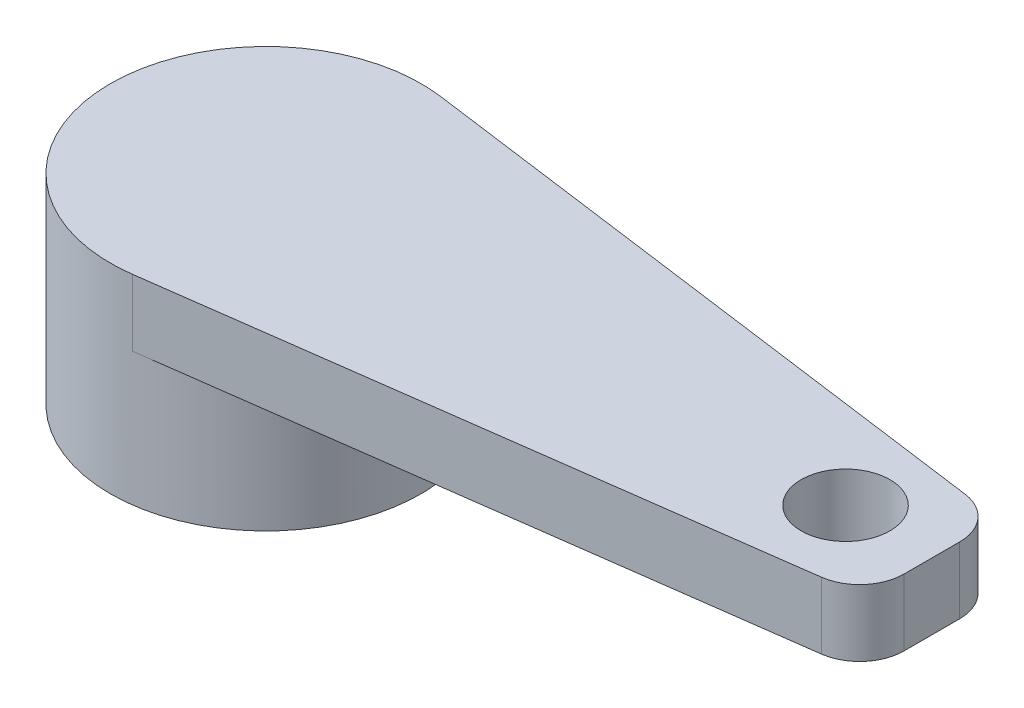
SolidWorks part; units mm, degrees
material "Zero density"
ref_plane "Piano frontale" through (0, 0, 0) normal (0, 0, 1) x (1, 0, 0)
ref_plane "Piano superiore" through (0, 0, 0) normal (0, 1, 0) x (1, 0, 0)
ref_plane "Piano destro" through (0, 0, 0) normal (1, 0, 0) x (0, 0, -1)
sketch "Schizzo1" plane through (0, 0, 0) normal (0, 1, 0) x (1, 0, 0)
  circle A0 centre (0, 0) radius 3.5
  dimension "D1" = 7
extrude "Estrusione-Estrusione1" add sketch "Schizzo1" along normal blind 3
sketch "Schizzo2" plane through (0, 3, 0) normal (0, 1, 0) x (1, 0, 0)
  line L0 (0, 0) -> (15, 0) construction
  line L5 (15, 1.5) -> (15, -1.5)
  line L6 (15, -1.5) -> (0.4698, -3.4683)
  line L7 (0.4698, 3.4683) -> (15, 1.5)
  arc A2 (0.4698, 3.4683) -> (0.4698, -3.4683) centre (0, 0) ccw
  circle A3 centre (0, 0) radius 3.5 construction
  point P10 (15, 0)
  dimension "D1" = 15
  dimension "D2" = 3
extrude "Estrusione-Estrusione2" add sketch "Schizzo2" along normal blind 1.5
sketch "Schizzo3" plane through (0, 0, 0) normal (0, -1, 0) x (1, 0, 0)
  circle A0 centre (0, 0) radius 2.5
  dimension "D1" = 5
extrude "Taglio-Estrusione1" cut sketch "Schizzo3" against normal blind 2
fillet "Raccordo1" radius 1 2 edges at (15, 3.75, 1.5) (15, 3.75, -1.5)
sketch "Sketch2" plane through (0, 4.5, 0) normal (0, 1, 0) x (1, 0, 0)
  line L0 (15, -0.6263) -> (15, 0.6263) construction
  line L1 (14.1342, 1.6173) -> (0.4698, 3.4683) construction
  circle A0 centre (13, 0.0554) radius 1
  dimension "D1" = 2
  dimension "D2" = 2
  dimension "D3" = 1.7
extrude "Cut-Extrude1" cut sketch "Sketch2" against normal through all
